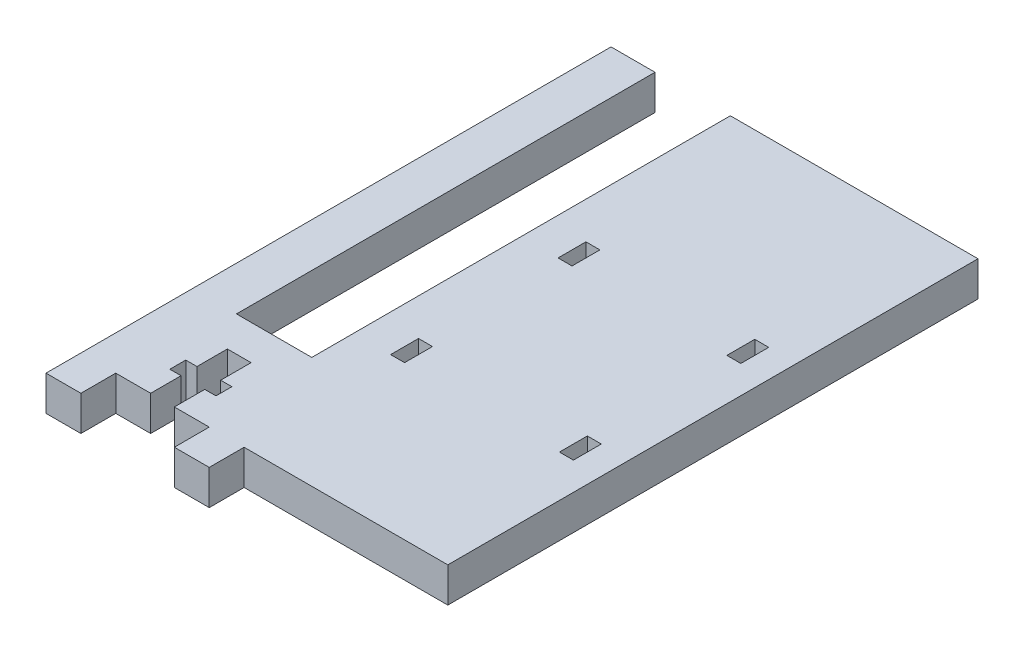
SolidWorks part; units mm, degrees
ref_plane "Front Plane" through (0, 0, 0) normal (0, 0, 1) x (1, 0, 0)
ref_plane "Top Plane" through (0, 0, 0) normal (0, 1, 0) x (1, 0, 0)
ref_plane "Right Plane" through (0, 0, 0) normal (1, 0, 0) x (0, 0, -1)
sketch "Sketch1" plane through (0, 0, 0) normal (0, 1, 0) x (1, 0, 0)
  line L0 (-6.858, 82.55) -> (-6.858, 6.35)
  line L1 (-6.858, 6.35) -> (6.858, 6.35)
  line L2 (6.858, 6.35) -> (6.858, 82.55)
  line L3 (14.859, -13.97) -> (45.593, -13.97)
  line L4 (6.858, 92.71) -> (14.859, 92.71) construction
  line L5 (14.859, 92.71) -> (45.593, 92.71) construction
  line L6 (-14.859, -13.97) -> (-14.859, 82.55)
  line L7 (-14.859, 82.55) -> (-6.858, 82.55)
  line L8 (14.859, 82.55) -> (45.593, 82.55)
  line L9 (14.859, 82.55) -> (14.859, -13.97) construction
  line L10 (45.593, 82.55) -> (45.593, -13.97) construction
  line L11 (45.593, 92.71) -> (51.943, 92.71) construction
  line L12 (45.593, 82.55) -> (51.943, 82.55)
  line L13 (51.943, 82.55) -> (51.943, -13.97)
  line L14 (51.943, -13.97) -> (45.593, -13.97)
  line L15 (14.859, 16.51) -> (45.593, 16.51) construction
  line L16 (14.859, 46.99) -> (45.593, 46.99) construction
  line L17 (30.226, -13.97) -> (30.226, 82.55) construction
  line L18 (13.589, 13.97) -> (16.129, 13.97)
  line L19 (13.589, 13.97) -> (13.589, 19.05)
  line L20 (13.589, 19.05) -> (16.129, 19.05)
  line L21 (16.129, 13.97) -> (16.129, 19.05)
  line L22 (13.589, 13.97) -> (16.129, 19.05) construction
  line L23 (13.589, 19.05) -> (16.129, 13.97) construction
  line L24 (46.863, 19.05) -> (44.323, 13.97) construction
  line L25 (46.863, 13.97) -> (44.323, 19.05) construction
  line L26 (44.323, 13.97) -> (44.323, 19.05)
  line L27 (46.863, 19.05) -> (44.323, 19.05)
  line L28 (46.863, 13.97) -> (46.863, 19.05)
  line L29 (46.863, 13.97) -> (44.323, 13.97)
  line L30 (46.863, 49.53) -> (44.323, 44.45) construction
  line L31 (13.589, 44.45) -> (16.129, 44.45)
  line L32 (13.589, 44.45) -> (13.589, 49.53)
  line L33 (13.589, 49.53) -> (16.129, 49.53)
  line L34 (16.129, 44.45) -> (16.129, 49.53)
  line L35 (13.589, 44.45) -> (16.129, 49.53) construction
  line L36 (13.589, 49.53) -> (16.129, 44.45) construction
  line L37 (46.863, 44.45) -> (44.323, 49.53) construction
  line L38 (44.323, 44.45) -> (44.323, 49.53)
  line L39 (46.863, 49.53) -> (44.323, 49.53)
  line L40 (46.863, 44.45) -> (46.863, 49.53)
  line L41 (46.863, 44.45) -> (44.323, 44.45)
  line L42 (14.859, 82.55) -> (6.858, 82.55)
  point P32 (30.226, 46.99)
  line B0 (-8.509, -13.97) -> (-8.509, -20.32)
  line B1 (-8.509, -20.32) -> (-14.859, -20.32)
  line B2 (-14.859, -20.32) -> (-14.859, -13.97)
  line B3 (-2.159, -13.97) -> (-2.159, -8.435)
  line B4 (-2.159, -8.435) -> (-4.2, -8.435)
  line B5 (-4.2, -8.435) -> (-4.2, -5.535)
  line B6 (-4.2, -5.535) -> (-2.159, -5.535)
  line B7 (-2.159, -5.535) -> (-2.159, 0)
  line B8 (-2.159, 0) -> (2.159, 0)
  line B9 (2.159, 0) -> (2.159, -5.535)
  line B10 (2.159, -5.535) -> (4.2, -5.535)
  line B11 (4.2, -5.535) -> (4.2, -8.435)
  line B12 (4.2, -8.435) -> (2.159, -8.435)
  line B13 (2.159, -8.435) -> (2.159, -13.97)
  line B14 (0, 0) -> (0, -13.97) construction
  line B15 (8.509, -13.97) -> (2.159, -13.97)
  line B16 (14.859, -20.32) -> (14.859, -13.97)
  line B17 (-8.509, -13.97) -> (-2.159, -13.97)
  line B18 (8.509, -20.32) -> (14.859, -20.32)
  line B19 (8.509, -13.97) -> (8.509, -20.32)
  dimension "D1" = 6.35
  dimension "D2" = 76.2
  dimension "D3" = 13.716
  dimension "D5" = 30.734
  dimension "D6" = 6.35
  dimension "D8" = 106.68
  dimension "D9" = 30.48
  dimension "D10" = 30.48
  dimension "D11" = 5.08
  dimension "D12" = 2.54
  dimension "D13" = 5.08
  dimension "D14" = 2.54
sketch_block_instance "Male T-slot assembly-1"
sketch_block "Male T-slot assembly" parameters "D1"=6.35, "D2"=6.35, "D3"=4.318, "D4"=2.9, "D5"=8.4, "D6"=13.97, "D7"=6.35
extrude "Boss-Extrude1" add sketch "Sketch1" along normal blind 6.35
